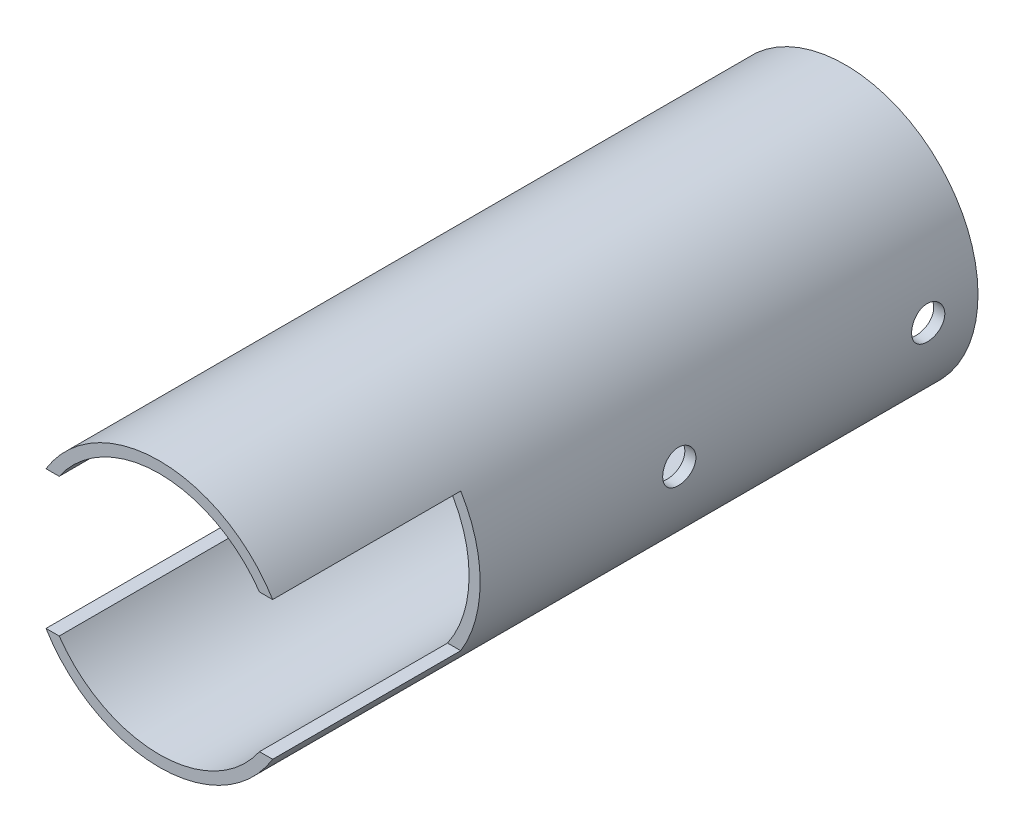
SolidWorks part; units mm, degrees
material "6061-O (SS)"
ref_plane "前视基准面" through (0, 0, 0) normal (0, 0, 1) x (1, 0, 0)
ref_plane "上视基准面" through (0, 0, 0) normal (0, 1, 0) x (1, 0, 0)
ref_plane "右视基准面" through (0, 0, 0) normal (1, 0, 0) x (0, 0, -1)
sketch "草图1" plane through (0, 0, 0) normal (0, 0, 1) x (1, 0, 0)
  circle A0 centre (0, 0) radius 22
  circle A1 centre (0, 0) radius 24
  dimension "D1" = 44
  dimension "D2" = 48
extrude "凸台-拉伸1" add sketch "草图1" along normal blind 124
sketch "草图2" plane through (0, 0, 0) normal (0, 1, 0) x (1, 0, 0)
  circle A0 centre (0, 0) radius 3.5
  dimension "D1" = 7
extrude "切除-拉伸1" cut sketch "草图2" against normal blind 100
sketch "草图3" plane through (0, 0, 0) normal (1, 0, 0) x (0, 0, -1)
  line L0 (-124, 24) -> (-124, -24) construction
  line L1 (-90, -12.5) -> (-158, -12.5)
  line L2 (-90, -12.5) -> (-90, 12.5)
  line L3 (-90, 12.5) -> (-158, 12.5)
  line L4 (-158, -12.5) -> (-158, 12.5)
  line L5 (-90, -12.5) -> (-158, 12.5) construction
  line L6 (-90, 12.5) -> (-158, -12.5) construction
  point P0 (-124, 0)
  dimension "D1" = 25
  dimension "D2" = 68
extrude "切除-拉伸2" cut sketch "草图3" against normal through all both and the other way through all
sketch "草图4" plane through (0, 0, 0) normal (1, 0, 0) x (0, 0, -1)
  circle A0 centre (-9, 0) radius 3
  circle A1 centre (-54, 0) radius 3
  dimension "D1" = 6
  dimension "D2" = 6
  dimension "D4" = 45
  dimension "D3" = 9
extrude "切除-拉伸3" cut sketch "草图4" against normal through all both and the other way through all
